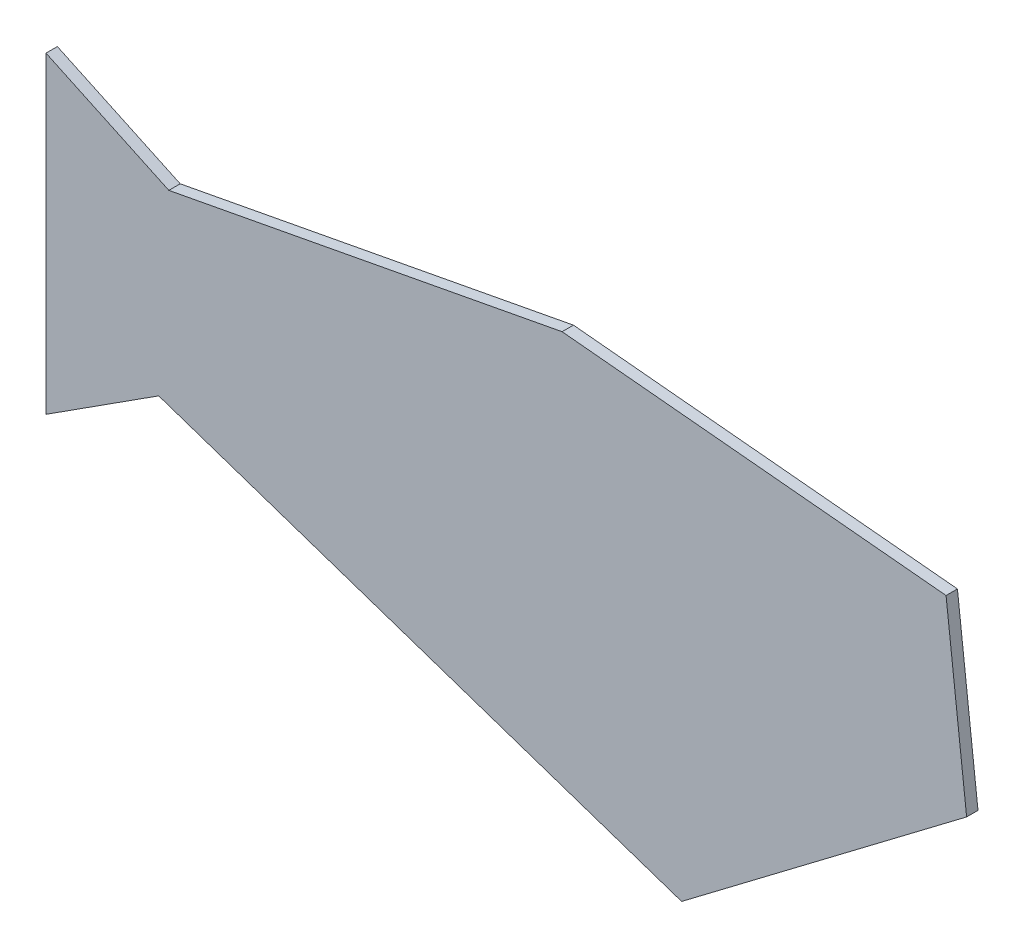
SolidWorks part; units mm, degrees
ref_plane "Спереди" through (0, 0, 0) normal (0, 0, 1) x (1, 0, 0)
ref_plane "Сверху" through (0, 0, 0) normal (0, 1, 0) x (1, 0, 0)
ref_plane "Справа" through (0, 0, 0) normal (1, 0, 0) x (0, 0, -1)
sketch "Эскиз1" plane through (-2.4428, 0.0155, 0) normal (0, 0, 1) x (1, 0, 0)
  line L0 (-32.435, 12.6383) -> (-32.435, -14.8739)
  line L1 (-32.435, -14.8739) -> (-22.5205, -8.5108)
  line L2 (-22.5205, -8.5108) -> (23.466, -24.0243)
  line L3 (23.466, -24.0243) -> (48.5299, -5.0571)
  line L4 (48.5299, -5.0571) -> (46.7213, 10.9064)
  line L5 (46.7213, 10.9064) -> (12.9508, 14.1134)
  line L6 (12.9508, 14.1134) -> (-21.6315, 7.586)
  line L7 (-21.6315, 7.586) -> (-32.435, 12.6383)
extrude "Бобышка-Вытянуть1" add sketch "Эскиз1" along normal blind 1
